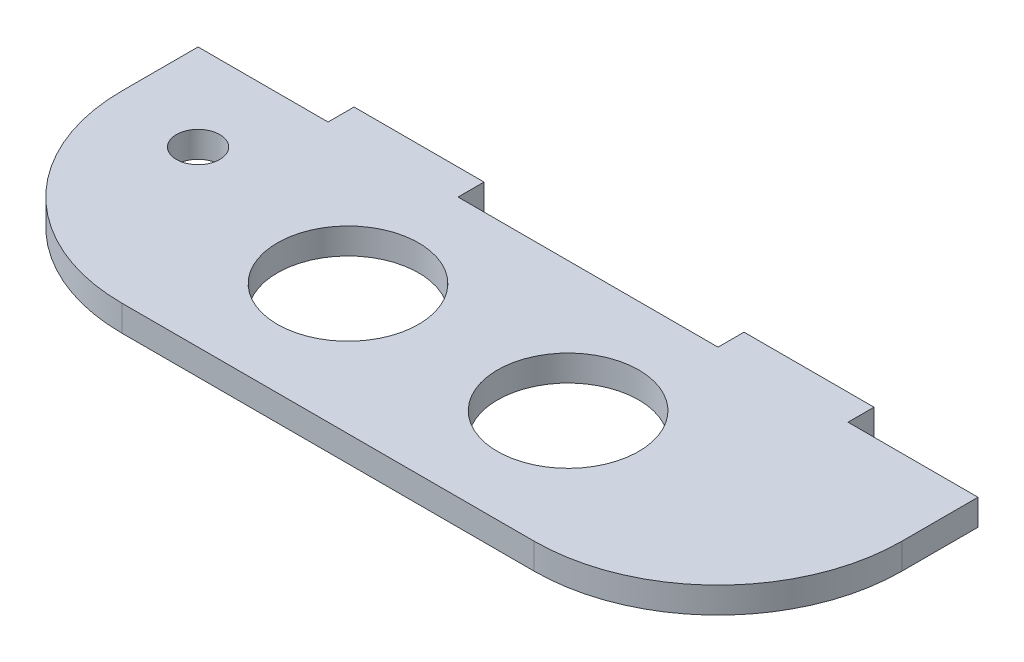
SolidWorks part; units mm, degrees
material "3mm Birch Ply Wood"
ref_plane "Front Plane" through (0, 0, 0) normal (0, 0, 1) x (1, 0, 0)
ref_plane "Top Plane" through (0, 0, 0) normal (0, 1, 0) x (1, 0, 0)
ref_plane "Right Plane" through (0, 0, 0) normal (1, 0, 0) x (0, 0, -1)
sketch "Sketch1" plane through (0, 0, 0) normal (0, 1, 0) x (1, 0, 0)
  line L0 (-45, 15) -> (-30, 15)
  line L1 (-45, -15) -> (45, -15)
  line L2 (-45, -15) -> (-45, 15)
  line L4 (45, -15) -> (45, 15)
  line L5 (-30, 15) -> (-30, 18)
  line L6 (-30, 18) -> (-15, 18)
  line L7 (-15, 18) -> (-15, 15)
  line L8 (-15, 15) -> (15, 15)
  line L9 (0, -15) -> (0, 15) construction
  line L10 (15, 18) -> (15, 15)
  line L11 (30, 18) -> (15, 18)
  line L12 (30, 15) -> (30, 18)
  line L13 (45, 15) -> (30, 15)
  point P0 (0, 0)
extrude "Boss-Extrude1" add sketch "Sketch1" along normal blind 3
sketch "Sketch2" plane through (0, 0, 0) normal (0, 1, 0) x (1, 0, 0)
  line L0 (0, -15) -> (0, 0) construction
  line L1 (-45, -15) -> (45, -15) construction
  line L2 (0, 0) -> (-12.7, 0) construction
  circle A0 centre (-12.7, 0) radius 8.15
  circle A1 centre (12.7, 0) radius 8.15
extrude "Cut-Extrude4" cut sketch "Sketch2" along normal through all
sketch "Sketch3" plane through (0, 3, 0) normal (0, 1, 0) x (1, 0, 0)
  line L1 (-45, 15) -> (-35, 15) construction
  line L2 (-45, 15) -> (-45, 5) construction
  line L3 (-45, 5) -> (-35, 5) construction
  line L4 (-35, 15) -> (-35, 5) construction
  circle A0 centre (-35, 5) radius 2.5
extrude "Cut-Extrude5" cut sketch "Sketch3" against normal blind 10
sketch "Sketch4" plane through (0, 3, 0) normal (0, 1, 0) x (1, 0, 0)
  line L0 (-45, 6.2132) -> (-45, -15)
  line L1 (-45, -15) -> (-23.7868, -15)
  line L2 (-45, 6.2132) -> (-45, -15)
  line L3 (0, -15) -> (0, 15) construction
  line L4 (-45, -15) -> (45, -15) construction
  line L5 (15, 15) -> (-15, 15) construction
  line L6 (45, 6.2132) -> (45, -15)
  line L7 (45, -15) -> (23.7868, -15)
  line L8 (45, 6.2132) -> (45, -15)
  arc A0 (-45, 6.2132) -> (-23.7868, -15) centre (-23.7868, 6.2132) ccw
  arc A1 (45, 6.2132) -> (23.7868, -15) centre (23.7868, 6.2132) cw
  line M15 (-45, 15) -> (-45, -15)
  line M16 (-45, -15) -> (45, -15)
  line M17 (45, -15) -> (45, 15)
extrude "Cut-Extrude6" cut sketch "Sketch4" against normal blind 10 contours A0 M15 M16 | A1 M17 M16
